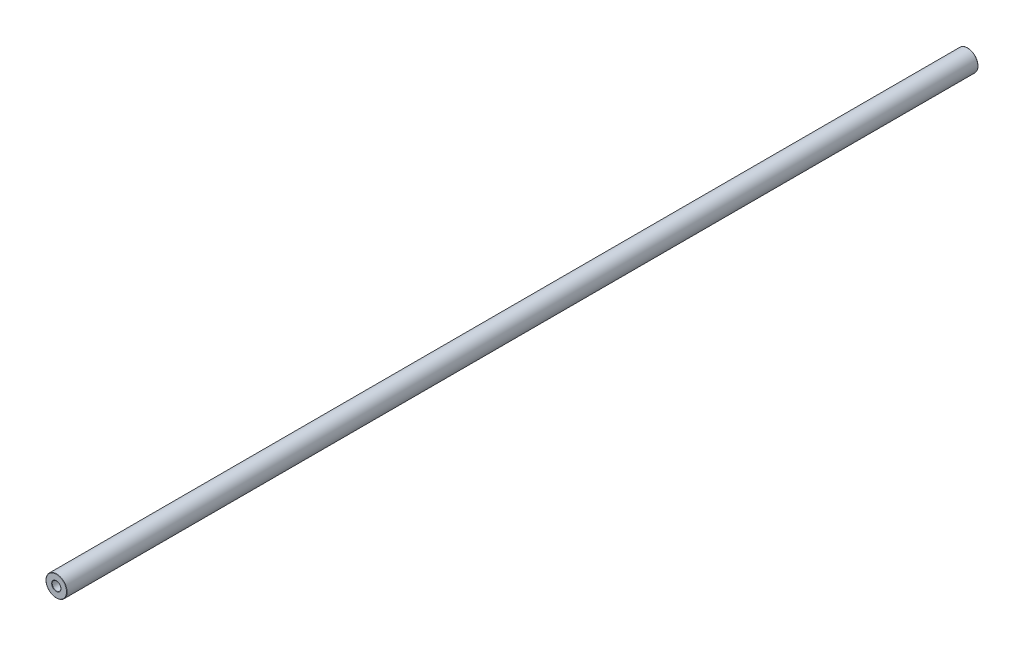
SolidWorks part; units mm, degrees
material "Alloy Steel"
ref_plane "Front Plane" through (0, 0, 0) normal (0, 0, 1) x (1, 0, 0)
ref_plane "Top Plane" through (0, 0, 0) normal (0, 1, 0) x (1, 0, 0)
ref_plane "Right Plane" through (0, 0, 0) normal (1, 0, 0) x (0, 0, -1)
sketch "Sketch1" plane through (0, 0, 0) normal (0, 0, 1) x (1, 0, 0)
  circle A0 centre (0, 0) radius 3
  dimension "D1" = 6
extrude "Extrude1" add sketch "Sketch1" along normal blind 260
sketch "Sketch2" plane through (0, 0, 260) normal (0, 0, 1) x (1, 0, 0)
  circle A0 centre (0, 0) radius 1.25
  dimension "D1" = 2.5
extrude "Cut-Extrude1" cut sketch "Sketch2" against normal blind 20
sketch "Sketch3" plane through (0, 0, 0) normal (0, 0, -1) x (-1, 0, 0)
  circle A0 centre (0, 0) radius 1.25
  dimension "D1" = 2.5
extrude "Cut-Extrude2" cut sketch "Sketch3" against normal blind 20
fillet "Fillet1" radius 0.1 4 edges at (-1.25, 0, 0) (3, 0, 0) (3, 0, 260) (1.25, 0, 260)
